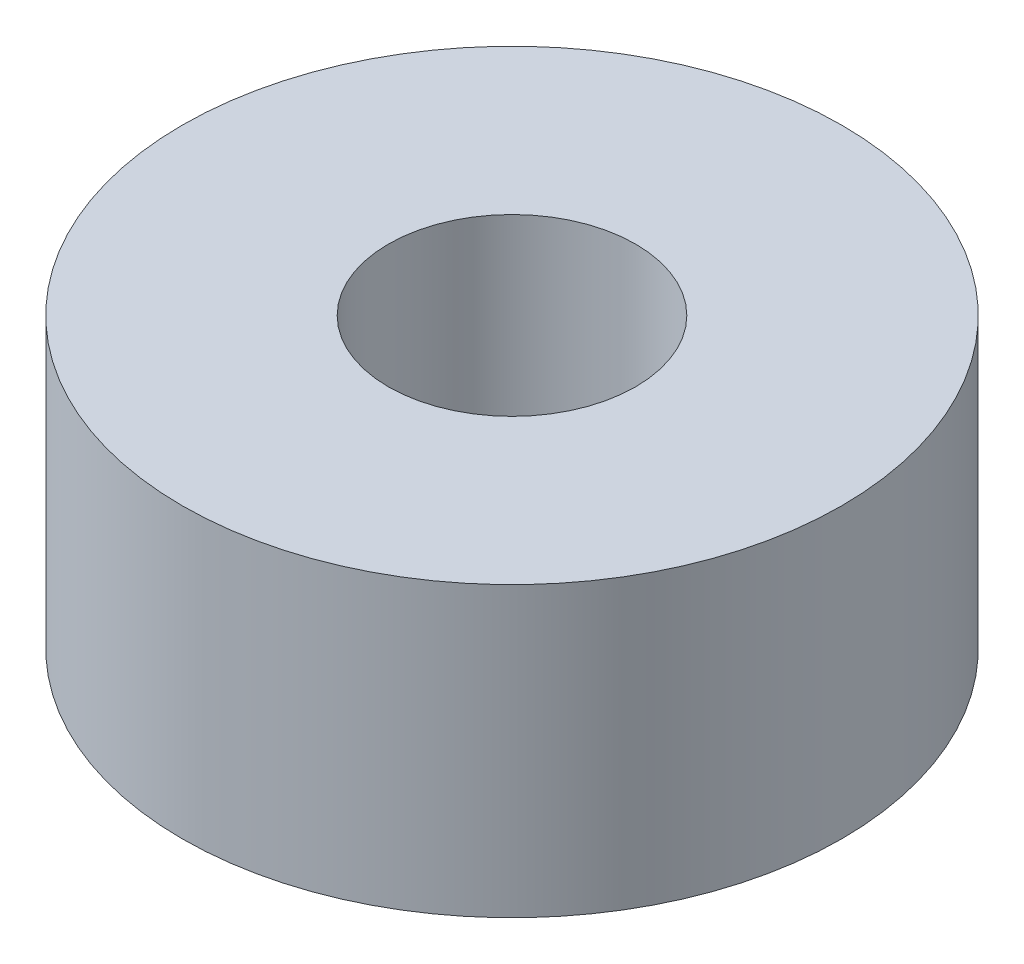
SolidWorks part; units mm, degrees
material "AISI 1020"
ref_plane "Front Plane" through (0, 0, 0) normal (0, 0, 1) x (1, 0, 0)
ref_plane "Top Plane" through (0, 0, 0) normal (0, 1, 0) x (1, 0, 0)
ref_plane "Right Plane" through (0, 0, 0) normal (1, 0, 0) x (0, 0, -1)
sketch "Sketch1" plane through (0, 0, 0) normal (0, 1, 0) x (1, 0, 0)
  circle A0 centre (0, 0) radius 1.5
  circle A1 centre (0, 0) radius 4
  dimension "D1" = 3
  dimension "D2" = 8
extrude "Boss-Extrude1" add sketch "Sketch1" along normal blind 3.5
